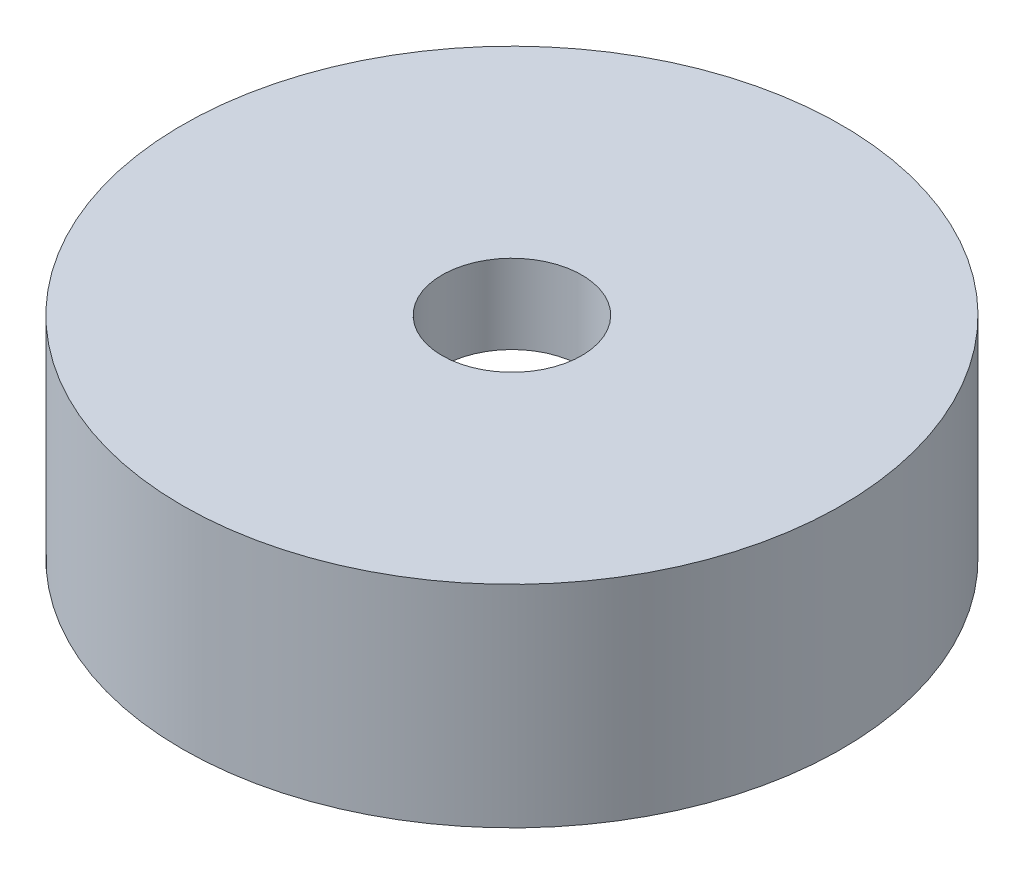
SolidWorks part; units mm, degrees
ref_plane "Front Plane" through (0, 0, 0) normal (0, 0, 1) x (1, 0, 0)
ref_plane "Top Plane" through (0, 0, 0) normal (0, 1, 0) x (1, 0, 0)
ref_plane "Right Plane" through (0, 0, 0) normal (1, 0, 0) x (0, 0, -1)
sketch "Sketch1" plane through (0, 0, 0) normal (0, 1, 0) x (1, 0, 0)
  circle A0 centre (0, 0) radius 10
  circle A1 centre (0, 0) radius 12.5
  dimension "D1" = 20
  dimension "D2" = 25
extrude "Boss-Extrude1" add sketch "Sketch1" along normal blind 5
sketch "Sketch2" plane through (0, 5, 0) normal (0, 1, 0) x (1, 0, 0)
  circle A0 centre (0, 0) radius 12.5
  circle A1 centre (0, 0) radius 2.65
  dimension "D1" = 25
  dimension "D2" = 5.3
extrude "Boss-Extrude2" add sketch "Sketch2" along normal blind 3
